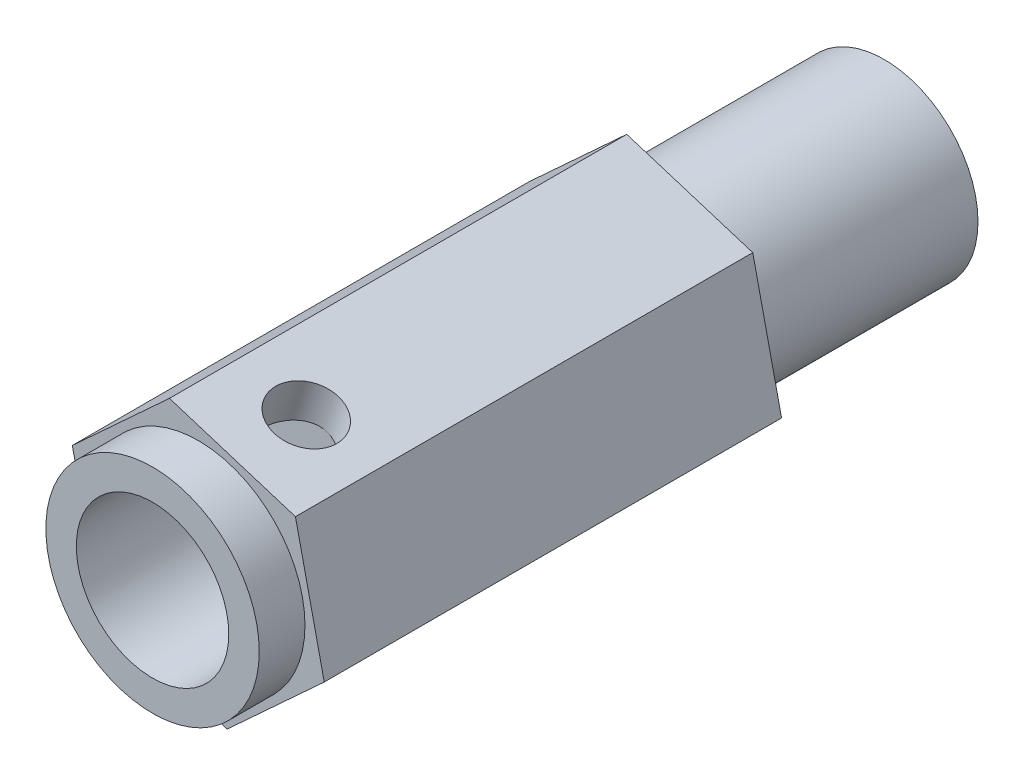
SolidWorks part; units mm, degrees
ref_plane "前视基准面" through (0, 0, 0) normal (0, 0, 1) x (1, 0, 0)
ref_plane "上视基准面" through (0, 0, 0) normal (0, 1, 0) x (1, 0, 0)
ref_plane "右视基准面" through (0, 0, 0) normal (1, 0, 0) x (0, 0, -1)
sketch "草图1" plane through (0, 0, 0) normal (0, 0, 1) x (1, 0, 0)
  circle A0 centre (0, 0) radius 6.15
  dimension "D1" = 12.3
extrude "凸台-拉伸1" add sketch "草图1" along normal blind 15
sketch "草图2" plane through (0, 0, 15) normal (0, 0, 1) x (1, 0, 0)
  line L1 (6.3739, 5.8628) -> (-1.8904, 8.4514)
  line L2 (-1.8904, 8.4514) -> (-8.2643, 2.5886)
  line L3 (-8.2643, 2.5886) -> (-6.3739, -5.8628)
  line L4 (-6.3739, -5.8628) -> (1.8904, -8.4514)
  line L5 (1.8904, -8.4514) -> (8.2643, -2.5886)
  line L6 (8.2643, -2.5886) -> (6.3739, 5.8628)
  circle A0 centre (0, 0) radius 7.5 construction
  dimension "D1" = 15
extrude "凸台-拉伸2" add sketch "草图2" along normal blind 30
sketch "草图3" plane through (0, 0, 45) normal (0, 0, 1) x (1, 0, 0)
  circle A0 centre (0, 0) radius 7
  dimension "D1" = 14
extrude "凸台-拉伸3" add sketch "草图3" along normal blind 3
sketch "草图4" plane through (0, 0, 48) normal (0, 0, 1) x (1, 0, 0)
  circle A0 centre (0, 0) radius 5
  dimension "D1" = 10
extrude "切除-拉伸1" cut sketch "草图4" against normal blind 10
hole_wizard "M5x0.8 螺纹孔1" positions "草图6" profile "草图5" tap size "M5x0.8" standard "JIS"
sketch "草图6" plane through (2.2418, 7.1571, 0) normal (0.2989, 0.9543, 0) x (-0.9543, 0.2989, 0)
  point P1 (0, 40.1584)
cosmetic thread "孔螺蚊线1" parameters "D2"=5
sketch "草图5" plane through (2.2418, 7.1571, 40.1584) normal (0, 0, 1) x (-0.9543, 0.2989, 0)
  line L0 (0, 0) -> (0, 2.5)
  line L1 (0, 2.5) -> (2.1, 2.5)
  line L2 (2.1, 2.5) -> (2.1, 0)
  line L5 (2.1, 0) -> (0, 0)
  line L11 (0, -6.35) -> (0, 107.95) construction
  dimension "通孔螺纹孔钻头直径" = 4.2
  dimension "通孔螺纹孔钻头深度" = 2.5
